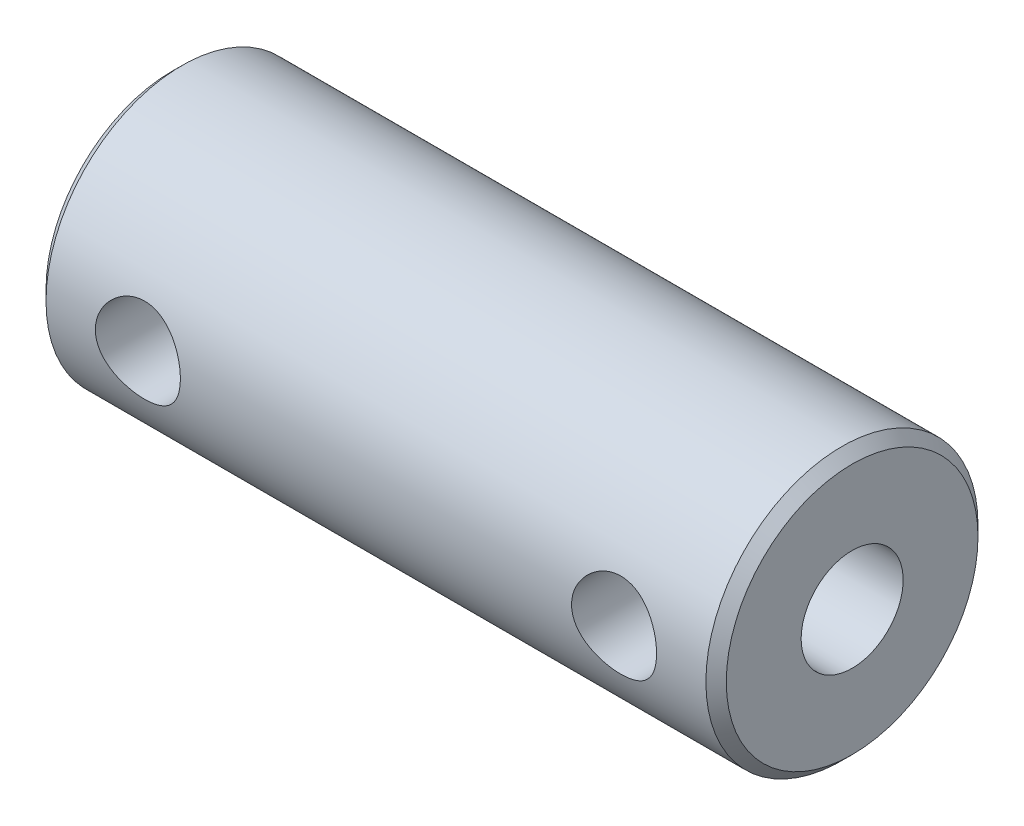
SolidWorks part; units mm, degrees
material "1060-O (SS)"
ref_plane "Plan de face" through (0, 0, 0) normal (0, 0, 1) x (1, 0, 0)
ref_plane "Plan de dessus" through (0, 0, 0) normal (0, 1, 0) x (1, 0, 0)
ref_plane "Plan de droite" through (0, 0, 0) normal (1, 0, 0) x (0, 0, -1)
sketch "Esquisse1" plane through (0, 0, 0) normal (0, 0, 1) x (1, 0, 0)
  line L0 (-9.08, 0) -> (10.7979, 0) construction
  line L1 (-10, 3.7) -> (-10, 2)
  line L2 (-10, 2) -> (0, 2)
  line L3 (0, 2) -> (0, 1.5)
  line L4 (0, 1.5) -> (10, 1.5)
  line L5 (10, 1.5) -> (10, 3.7)
  line L6 (10, 3.7) -> (9.7, 4)
  line L7 (9.7, 4) -> (-9.7, 4)
  line L8 (-9.7, 4) -> (-10, 3.7)
  dimension "D1" = 2
  dimension "D2" = 1.5
  dimension "D3" = 4
  dimension "D4" = 10
  dimension "D5" = 20
  dimension "D6" = 0.3
  dimension "D7" = 0.3
  dimension "D8" = 0.3
  dimension "D9" = 0.3
revolve "Révolution1" add sketch "Esquisse1" angle 360 about L0
ref_plane "Plan1" through (0, 0, 6.1) normal (0, 0, 1) x (1, 0, 0)
sketch "Esquisse2" plane through (0, 0, 6.1) normal (0, 0, 1) x (1, 0, 0)
  line L0 (-13.257, 0) -> (14.5306, 0) construction
  circle A0 centre (-7, 0) radius 1.25
  circle A1 centre (7, 0) radius 1.25
  dimension "D1" = 2.5
  dimension "D2" = 2.5
  dimension "D3" = 7
  dimension "D4" = 7
extrude "Enlèv. mat.-Extru.1" cut sketch "Esquisse2" against normal blind 5
